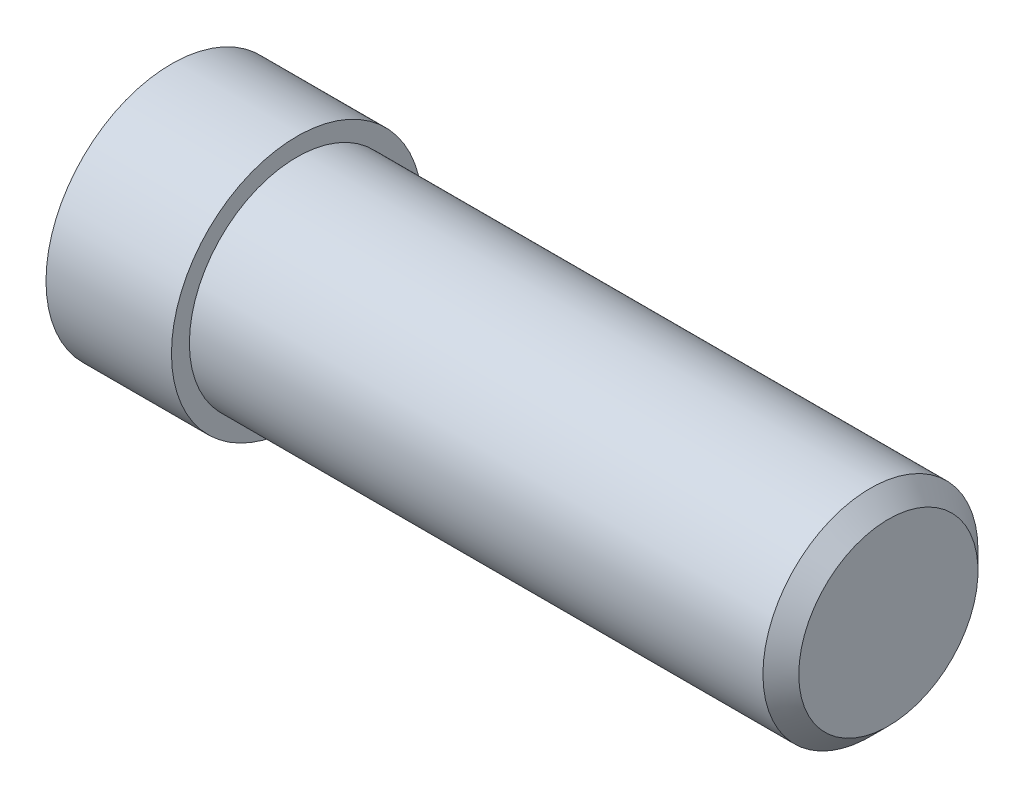
SolidWorks part; units mm, degrees
material "Cast Alloy Steel"
ref_plane "Front Plane" through (0, 0, 0) normal (0, 0, 1) x (1, 0, 0)
ref_plane "Top Plane" through (0, 0, 0) normal (0, 1, 0) x (1, 0, 0)
ref_plane "Right Plane" through (0, 0, 0) normal (1, 0, 0) x (0, 0, -1)
sketch "Sketch1" plane through (0, 0, 0) normal (0, 0, 1) x (1, 0, 0)
  line L0 (0, 0) -> (0, 6)
  line L1 (0, 6) -> (-33, 6)
  line L2 (-33, 6) -> (-33, 7)
  line L3 (-33, 7) -> (-40, 7)
  line L4 (-40, 7) -> (-40, 0)
  line L5 (-40, 0) -> (0, 0)
  dimension "D1" = 33
  dimension "D2" = 7
  dimension "D3" = 7
  dimension "D4" = 6
revolve "Revolve1" add sketch "Sketch1" angle 360 about L5
chamfer "Chamfer1" distance 1 angle 45 1 edges at (0, 0, 6)
